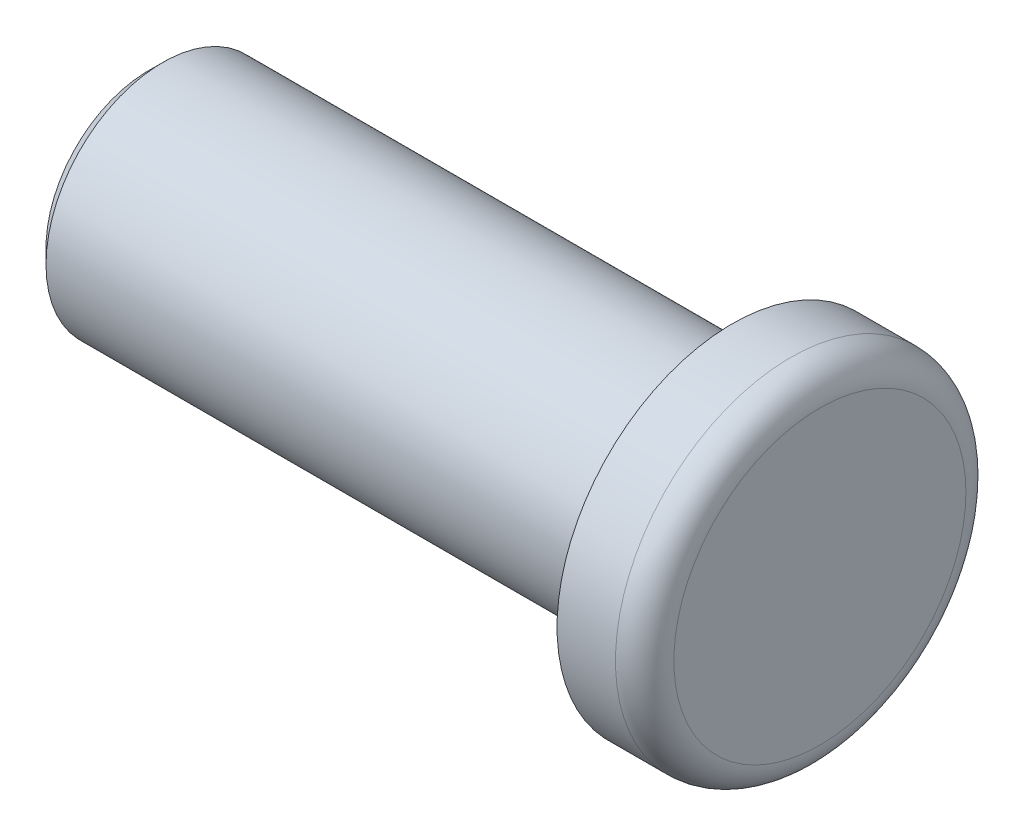
SolidWorks part; units mm, degrees
ref_plane "Front Plane" through (0, 0, 0) normal (0, 0, 1) x (1, 0, 0)
ref_plane "Top Plane" through (0, 0, 0) normal (0, 1, 0) x (1, 0, 0)
ref_plane "Right Plane" through (0, 0, 0) normal (1, 0, 0) x (0, 0, -1)
sketch "Sketch1" plane through (0, 0, 0) normal (1, 0, 0) x (0, 0, -1)
  circle A0 centre (0, 0) radius 6
  circle A1 centre (0, 0) radius 4
  dimension "D1" = 12
  dimension "D2" = 8
extrude "Boss-Extrude1" add sketch "Sketch1" along normal blind 3
sketch "Sketch2" plane through (3, 0, 0) normal (1, 0, 0) x (0, 0, -1)
  circle A0 centre (0, 0) radius 4
extrude "Boss-Extrude2" add sketch "Sketch2" against normal blind 23
fillet "Fillet1" radius 1 1 edges at (3, 0, -6)
chamfer "Chamfer1" distance 0.5 angle 45 1 edges at (-20, 0, -4)
